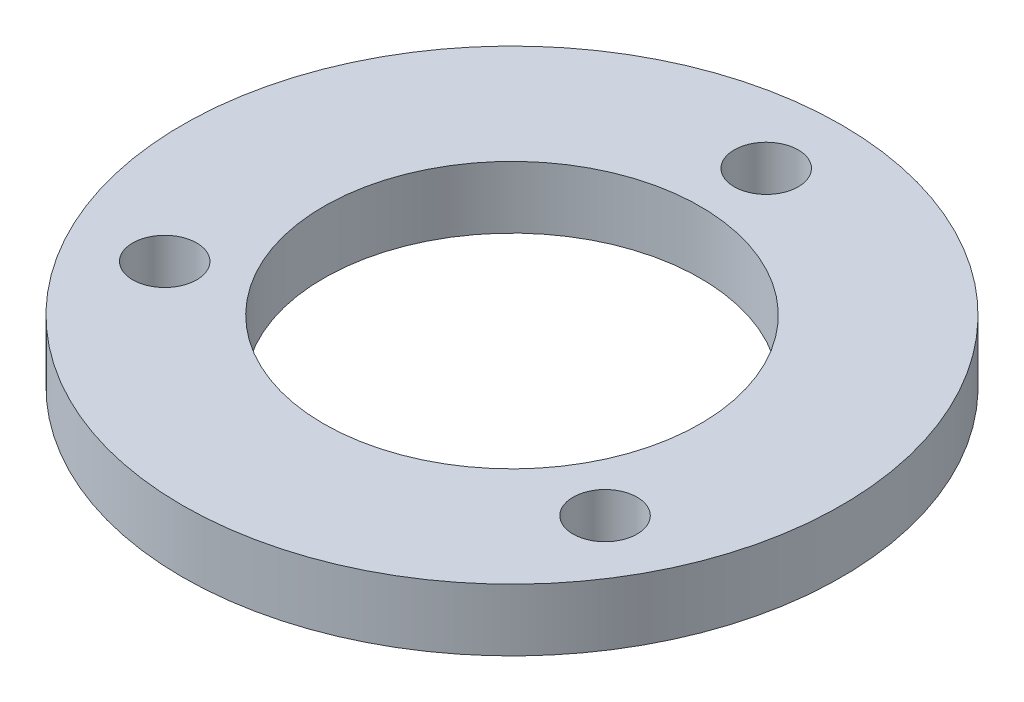
SolidWorks part; units mm, degrees
material "ABS"
ref_plane "前视基准面" through (0, 0, 0) normal (0, 0, 1) x (1, 0, 0)
ref_plane "上视基准面" through (0, 0, 0) normal (0, 1, 0) x (1, 0, 0)
ref_plane "右视基准面" through (0, 0, 0) normal (1, 0, 0) x (0, 0, -1)
other "Configuration Table"
sketch "草图1" plane through (0, 0, 0) normal (0, 1, 0) x (1, 0, 0)
  circle A0 centre (0, 0) radius 13.5 construction
  circle A1 centre (0, 0) radius 10
  circle A2 centre (0, 0) radius 17.5
  circle A3 centre (0, 13.5) radius 1.7
  circle A4 centre (11.6913, -6.75) radius 1.7
  circle A5 centre (-11.6913, -6.75) radius 1.7
  point P13 (0, 0)
  dimension "D1" = 27
  dimension "D2" = 20
  dimension "D3" = 35
  dimension "D4" = 3.4
extrude "凸台-拉伸1" add sketch "草图1" along normal blind 3.3
